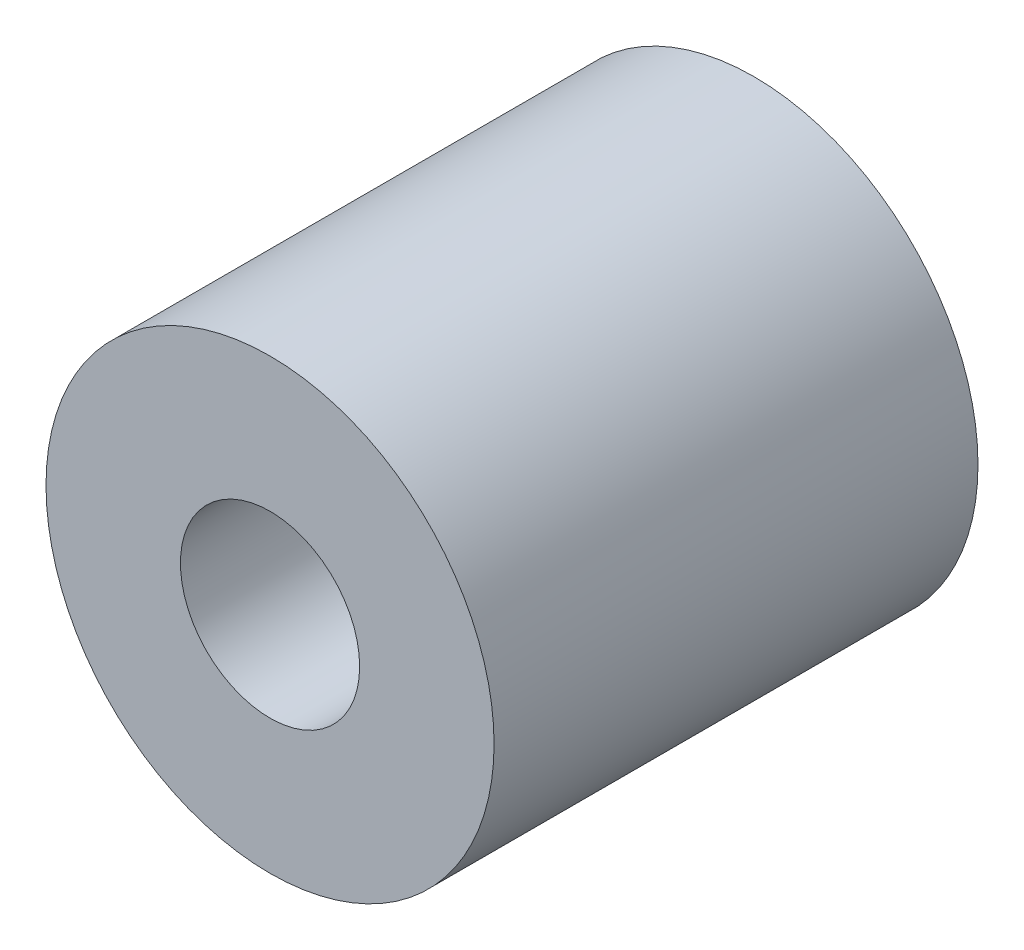
SolidWorks part; units mm, degrees
material "ABS"
ref_plane "Front Plane" through (0, 0, 0) normal (0, 0, 1) x (1, 0, 0)
ref_plane "Top Plane" through (0, 0, 0) normal (0, 1, 0) x (1, 0, 0)
ref_plane "Right Plane" through (0, 0, 0) normal (1, 0, 0) x (0, 0, -1)
sketch "Sketch1" plane through (0, 0, 0) normal (0, 0, 1) x (1, 0, 0)
  circle A0 centre (0, 0) radius 1.27
  circle A1 centre (0, 0) radius 3.175
  dimension "D1" = 2.54
  dimension "D2" = 6.35
extrude "Boss-Extrude1" add sketch "Sketch1" along normal blind 6.858
